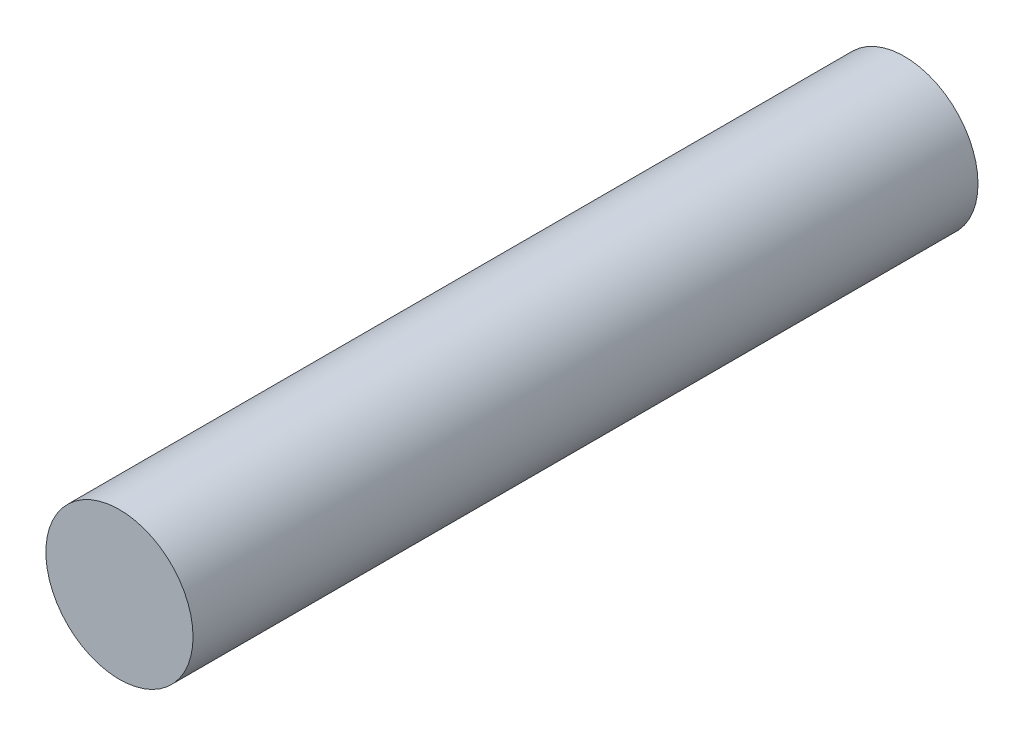
SolidWorks part; units mm, degrees
ref_plane "Front Plane" through (0, 0, 0) normal (0, 0, 1) x (1, 0, 0)
ref_plane "Top Plane" through (0, 0, 0) normal (0, 1, 0) x (1, 0, 0)
ref_plane "Right Plane" through (0, 0, 0) normal (1, 0, 0) x (0, 0, -1)
sketch "Sketch1" plane through (0, 0, 0) normal (0, 0, 1) x (1, 0, 0)
  circle A0 centre (0, 0) radius 4.7625
  dimension "D1" = 9.525
extrude "Boss-Extrude1" add sketch "Sketch1" against normal blind 50.8
